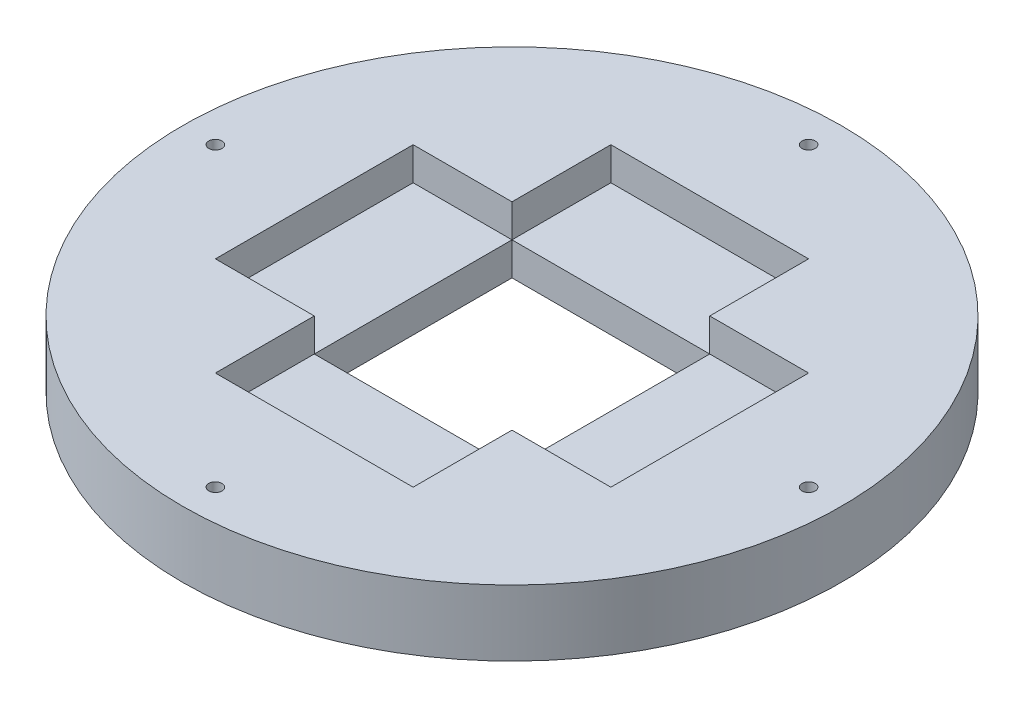
SolidWorks part; units mm, degrees
ref_plane "Plan de face" through (0, 0, 0) normal (0, 0, 1) x (1, 0, 0)
ref_plane "Plan de dessus" through (0, 0, 0) normal (0, 1, 0) x (1, 0, 0)
ref_plane "Plan de droite" through (0, 0, 0) normal (1, 0, 0) x (0, 0, -1)
sketch "Esquisse2" plane through (0, 0, 0) normal (0, 1, 0) x (1, 0, 0)
  line L1 (-60, 30) -> (60, 30)
  line L2 (-60, 30) -> (-60, -30)
  line L3 (-60, -30) -> (60, -30)
  line L4 (60, 30) -> (60, -30)
  line L5 (-30, 60) -> (30, 60)
  line L6 (-30, 60) -> (-30, -60)
  line L7 (-30, -60) -> (30, -60)
  line L8 (30, 60) -> (30, -60)
  circle A0 centre (0, 0) radius 100
  point P11 (0, 0)
  point P12 (0, 0)
  point P13 (0, 0)
  point P14 (0, 0)
  point P15 (0, 0)
  point P16 (0, 0)
  dimension "D1" = 200
  dimension "D2" = 120
  dimension "D3" = 60
  dimension "D4" = 120
  dimension "D5" = 60
extrude "Boss.-Extru.6" add sketch "Esquisse2" along normal blind 20 contours A0 L5 L8 L1 L4 L3 L7 L6 L2 | L6 L1 L2 L3 | L8 L3 L6 L7 | L1 L8 L3 L4 | L8 L5 L6 L1
sketch "Esquisse3" plane through (0, 20, 0) normal (0, 1, 0) x (1, 0, 0)
  line L18 (-30, 30) -> (30, 30)
  line L19 (-30, 30) -> (-30, 60)
  line L20 (-30, 60) -> (30, 60)
  line L21 (30, 30) -> (30, 60)
  line L22 (-30, -30) -> (30, -30)
  line L23 (-30, -30) -> (-30, -60)
  line L24 (-30, -60) -> (30, -60)
  line L25 (30, -30) -> (30, -60)
  line L26 (30, 30) -> (60, 30)
  line L27 (30, 30) -> (30, -30)
  line L28 (30, -30) -> (60, -30)
  line L29 (60, 30) -> (60, -30)
  line L30 (-30, 30) -> (-60, 30)
  line L31 (-30, 30) -> (-30, -30)
  line L32 (-30, -30) -> (-60, -30)
  line L33 (-60, 30) -> (-60, -30)
  line M17 (-30, 30) -> (30, 30)
  line M18 (30, 30) -> (30, -30)
  line M19 (30, -30) -> (-30, -30)
  line M20 (-30, -30) -> (-30, 30)
  dimension "D1" = 60
  dimension "D2" = 30
  dimension "D3" = 30
  dimension "D4" = 30
  dimension "D5" = 30
  dimension "D6" = 30
  dimension "D7" = 30
  dimension "D8" = 30
extrude "Enlèv. mat.-Extru.7" cut sketch "Esquisse3" against normal blind 10 contours L21 L20 L19 M17 | L29 L26 L28 M18 | L25 L23 L24 M19 | L30 L33 L32 M20
sketch "Esquisse7" plane through (0, 20, 0) normal (0, 1, 0) x (1, 0, 0)
  line L0 (-30, 60) -> (30, 60) construction
  line L1 (-30, 30) -> (-30, 60) construction
  line L2 (60, 30) -> (60, -30) construction
  line L3 (-30, -60) -> (30, -60) construction
  line L4 (-60, 30) -> (-60, -30) construction
  line L5 (-30, 30) -> (-60, 30) construction
  circle A0 centre (0, 90) radius 2
  circle A1 centre (90, 0) radius 2
  circle A2 centre (0, -90) radius 2
  circle A3 centre (-90, 0) radius 2
  point P8 (78.974, 0)
  point P11 (0, -80.0448)
  point P14 (-83.525, 0)
  dimension "D3" = 4
  dimension "D4" = 4
  dimension "D5" = 4
  dimension "D6" = 4
  dimension "D1" = 30
  dimension "D2" = 30
  dimension "D7" = 30
  dimension "D8" = 30
  dimension "D9" = 30
  dimension "D10" = 30
  dimension "D11" = 30
  dimension "D12" = 30
extrude "Enlèv. mat.-Extru.8" cut sketch "Esquisse7" against normal blind 20
